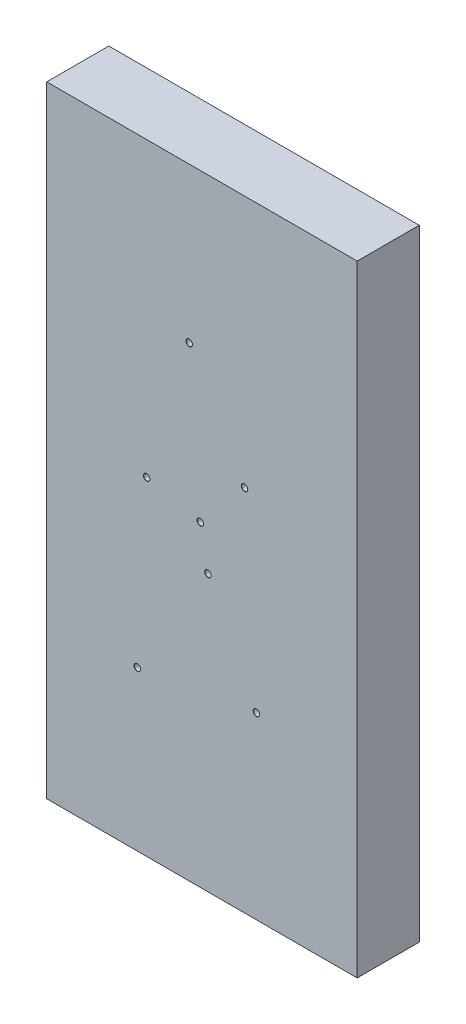
SolidWorks part; units mm, degrees
ref_plane "Front Plane" through (0, 0, 0) normal (0, 0, 1) x (1, 0, 0)
ref_plane "Top Plane" through (0, 0, 0) normal (0, 1, 0) x (1, 0, 0)
ref_plane "Right Plane" through (0, 0, 0) normal (1, 0, 0) x (0, 0, -1)
sketch "Sketch1" plane through (0, 0, 0) normal (0, 0, 1) x (1, 0, 0)
  line L1 (-25, 50) -> (25, 50)
  line L2 (-25, 50) -> (-25, -50)
  line L3 (-25, -50) -> (25, -50)
  line L4 (25, 50) -> (25, -50)
  line L5 (-25, 50) -> (25, -50) construction
  line L6 (-25, -50) -> (25, 50) construction
  point P0 (0, 0)
  dimension "D1" = 50
  dimension "D2" = 100
extrude "Boss-Extrude1" add sketch "Sketch1" along normal blind 10 contours L2 L3 L4 L1
hole_wizard "Ø1.0 (1) Diameter Hole1" positions "3DSketch1" profile "Sketch4" hole size "Ø1.0" standard "ISO"
sketch3d "3DSketch1"
  point P0 (0, 0, 0)
  point P3 (0, 0, 0)
  point P5 (-0.2741, 0.9594, 10)
  point P7 (0, 0, 0)
  point P9 (0, 0, 0)
  point P11 (0.9594, -5.6194, 10)
  point P13 (0.9594, -5.6194, 10)
  point P15 (-8.9088, 2.8782, 10)
  point P17 (6.8529, 9.3199, 10)
  point P19 (-2.0559, 25.0816, 10)
  point P21 (8.7717, -21.1069, 10)
  point P23 (-10.4164, -24.3963, 10)
sketch "Sketch4" plane through (-10.4164, -24.3963, 10) normal (1, 0, 0) x (0, -1, 0)
  line L0 (0, 0) -> (0, 10)
  line L1 (0, 10) -> (0.5, 10)
  line L2 (0.5, 10) -> (0.5, 0.025)
  line L3 (0.5, 0.025) -> (0.525, 0)
  line L5 (0.525, 0) -> (0, 0)
  line L6 (-0.5, 0.025) -> (-0.525, 0) construction
  line L11 (0, -6.35) -> (0, 107.95) construction
  dimension "Thru Hole Dia." = 1
  dimension "Thru Hole Depth" = 10
  dimension "Near C'Sink Dia." = 1.05
  dimension "Near C'Sink Angle" = 90
